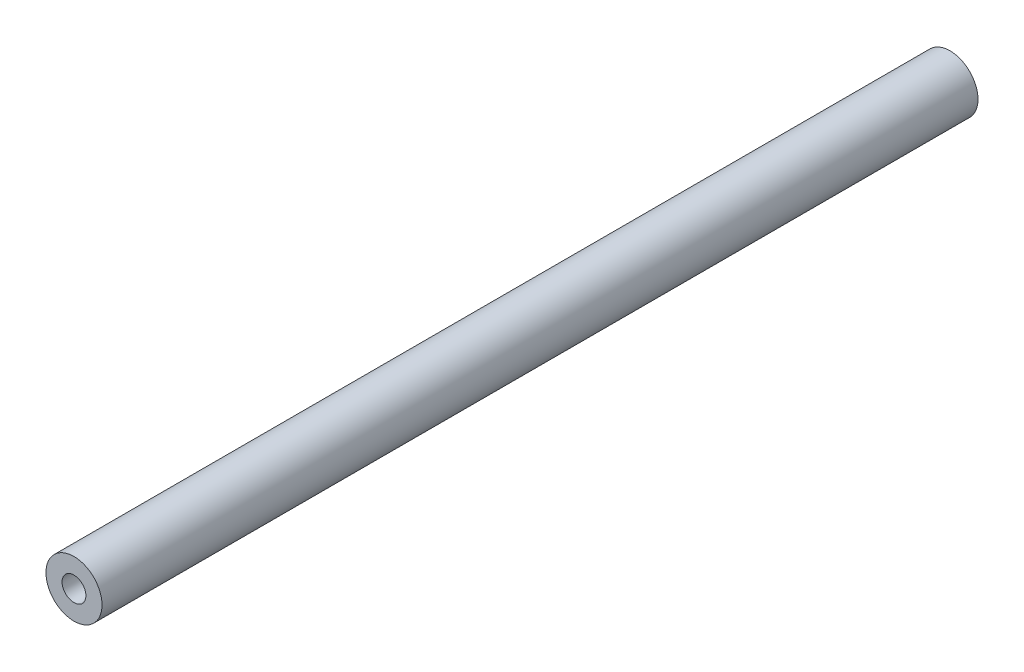
SolidWorks part; units mm, degrees
ref_plane "前视基准面" through (0, 0, 0) normal (0, 0, 1) x (1, 0, 0)
ref_plane "上视基准面" through (0, 0, 0) normal (0, 1, 0) x (1, 0, 0)
ref_plane "右视基准面" through (0, 0, 0) normal (1, 0, 0) x (0, 0, -1)
sketch "草图1" plane through (0, 0, 0) normal (0, 0, 1) x (1, 0, 0)
  circle A0 centre (0, 0) radius 8
  dimension "D1" = 16
extrude "凸台-拉伸1" add sketch "草图1" along normal blind 250
hole_wizard "M8 螺纹孔1" positions "3D草图2" profile "草图5" tap size "M8" standard "Gb"
sketch3d "3D草图2"
  line L0 (0, 0, 250) -> (0, 0, 0) construction
  point P0 (0, 0, 250)
  point P4 (0, 0, 0)
  point P8 (0, 0, 0)
  point P10 (0, 0, 0)
sketch "草图5" plane through (0, 0, 250) normal (1, 0, 0) x (0, -1, 0)
  line L0 (0, 0) -> (0, 28.2929)
  line L1 (0, 28.2929) -> (3.4, 26.25)
  line L2 (3.4, 26.25) -> (3.4, 0)
  line L5 (3.4, 0) -> (0, 0)
  line L10 (0, 28.2929) -> (-3.4, 26.25) construction
  line L11 (0, -6.35) -> (0, 107.95) construction
  dimension "螺纹孔钻头直径" = 6.8
  dimension "螺纹孔钻头深度" = 26.25
  dimension "导头角度" = 118
cosmetic thread "孔螺蚊线1"
cosmetic thread "孔螺蚊线2"
cosmetic thread "孔螺蚊线3"
cosmetic thread "孔螺蚊线4"
hole_wizard "M8 螺纹孔2" positions "草图7" profile "草图6" tap size "M8" standard "Gb"
sketch "草图7" plane through (0, 0, 0) normal (0, 0, -1) x (-1, 0, 0)
  point P0 (0, 0)
sketch "草图6" plane through (0, 0, 0) normal (1, 0, 0) x (0, 1, 0)
  line L0 (0, 0) -> (0, 28.2929)
  line L1 (0, 28.2929) -> (3.4, 26.25)
  line L2 (3.4, 26.25) -> (3.4, 0)
  line L5 (3.4, 0) -> (0, 0)
  line L10 (0, 28.2929) -> (-3.4, 26.25) construction
  line L11 (0, -6.35) -> (0, 107.95) construction
  dimension "螺纹孔钻头直径" = 6.8
  dimension "螺纹孔钻头深度" = 26.25
  dimension "导头角度" = 118
cosmetic thread "孔螺蚊线5"
